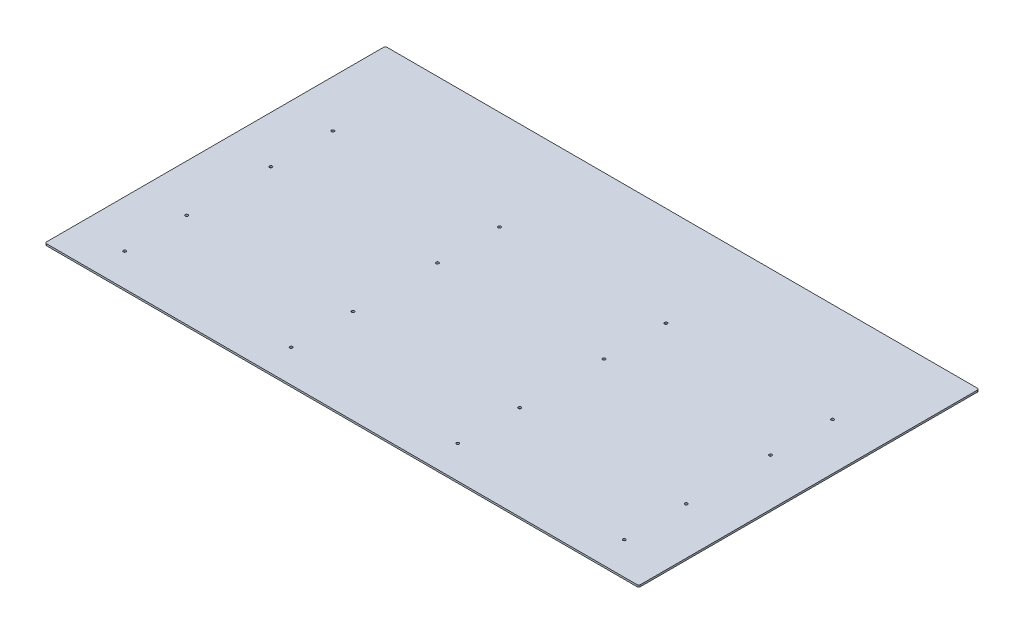
SolidWorks part; units mm, degrees
material "PE High Density"
ref_plane "Front Plane" through (0, 0, 0) normal (0, 0, 1) x (1, 0, 0)
ref_plane "Top Plane" through (0, 0, 0) normal (0, 1, 0) x (1, 0, 0)
ref_plane "Right Plane" through (0, 0, 0) normal (1, 0, 0) x (0, 0, -1)
sketch "Sketch1" plane through (0, 0, 0) normal (0, 1, 0) x (1, 0, 0)
  line L1 (-517.525, -298.45) -> (517.525, -298.45)
  line L2 (-520.7, -295.275) -> (-520.7, 295.275)
  line L3 (-517.525, 298.45) -> (517.525, 298.45)
  line L4 (520.7, -295.275) -> (520.7, 295.275)
  line L5 (-520.7, -298.45) -> (520.7, 298.45) construction
  line L6 (-520.7, 298.45) -> (520.7, -298.45) construction
  arc A0 (517.525, 298.45) -> (520.7, 295.275) centre (517.525, 295.275) cw
  arc A1 (517.525, -298.45) -> (520.7, -295.275) centre (517.525, -295.275) ccw
  arc A2 (-517.525, -298.45) -> (-520.7, -295.275) centre (-517.525, -295.275) cw
  arc A3 (-520.7, 295.275) -> (-517.525, 298.45) centre (-517.525, 295.275) cw
  point P0 (0, 0)
  dimension "D3" = 3.175
  dimension "D1" = 1041.4
  dimension "D2" = 596.9
extrude "Boss-Extrude1" add sketch "Sketch1" along normal blind 3.175
sketch "Sketch2" plane through (0, 0, 0) normal (0, -1, 0) x (1, 0, 0)
  line L0 (-517.525, 298.45) -> (517.525, 298.45) construction
  point P0 (-438.15, 241.2453)
  point P1 (-438.15, 132.5333)
  point P2 (0, 0)
  point P3 (-146.05, 241.2453)
  point P4 (0, 0)
  point P5 (-146.05, 132.5333)
  point P6 (0, 0)
  point P7 (146.05, 241.2453)
  point P8 (0, 0)
  point P9 (146.05, 132.5333)
  point P11 (438.15, 241.2453)
  point P13 (438.15, 132.5333)
  point P15 (438.15, -15.2947)
  point P17 (438.15, -124.0067)
  point P19 (146.05, -15.2947)
  point P21 (146.05, -124.0067)
  point P23 (-146.05, -15.2947)
  point P25 (-146.05, -124.0067)
  point P27 (-438.15, -15.2947)
  point P29 (-438.15, -124.0067)
  point P31 (0, 0)
  point P34 (0, 0)
  point P35 (0, 0)
  point P36 (0, 0)
  point P37 (0, 0)
  point P38 (0, 0)
  point P39 (0, 0)
  point P40 (0, 0)
  point P41 (0, 0)
  point P42 (0, 0)
  point P43 (0, 0)
  point P44 (0, 0)
  point P45 (0, 0)
  point P46 (0, 0)
  point P47 (0, 0)
  point P48 (0, 0)
  point P49 (0, 0)
  point P50 (0, 0)
  point P51 (0, 0)
  point P52 (0, 0)
  point P53 (0, 0)
  point P54 (0, 0)
  dimension "D1" = 108.712
  dimension "D2" = 108.712
  dimension "D3" = 147.828
  dimension "D4" = 57.2047
  dimension "D5" = 292.1
  dimension "D6" = 292.1
  dimension "D7" = 146.05
  dimension "D8" = 146.05
hole_wizard "#10 (0.1935) Diameter Hole1" positions "3DSketch1" profile "Sketch3" hole size "#10" standard "ANSI Inch" end condition through all
sketch3d "3DSketch1"
  point P0 (-438.15, 0, 241.2453)
  point P3 (-438.15, 0, 132.5333)
  point P6 (-146.05, 0, 241.2453)
  point P9 (-146.05, 0, 132.5333)
  point P12 (146.05, 0, 241.2453)
  point P15 (146.05, 0, 132.5333)
  point P18 (438.15, 0, 241.2453)
  point P21 (438.15, 0, 132.5333)
  point P24 (438.15, 0, -15.2947)
  point P27 (438.15, 0, -124.0067)
  point P30 (146.05, 0, -15.2947)
  point P33 (146.05, 0, -124.0067)
  point P36 (-146.05, 0, -124.0067)
  point P39 (-146.05, 0, -15.2947)
  point P42 (-438.15, 0, -15.2947)
  point P45 (-438.15, 0, -124.0067)
sketch "Sketch3" plane through (-438.15, 0, 241.2453) normal (1, 0, 0) x (0, 0, -1)
  line L0 (0, 0) -> (0, 3.175)
  line L1 (0, 3.175) -> (2.4574, 3.175)
  line L2 (2.4574, 3.175) -> (2.4574, 0)
  line L5 (2.4574, 0) -> (0, 0)
  line L11 (0, -6.35) -> (0, 107.95) construction
  dimension "Thru Hole Dia." = 4.9149
  dimension "Thru Hole Depth" = 3.175
